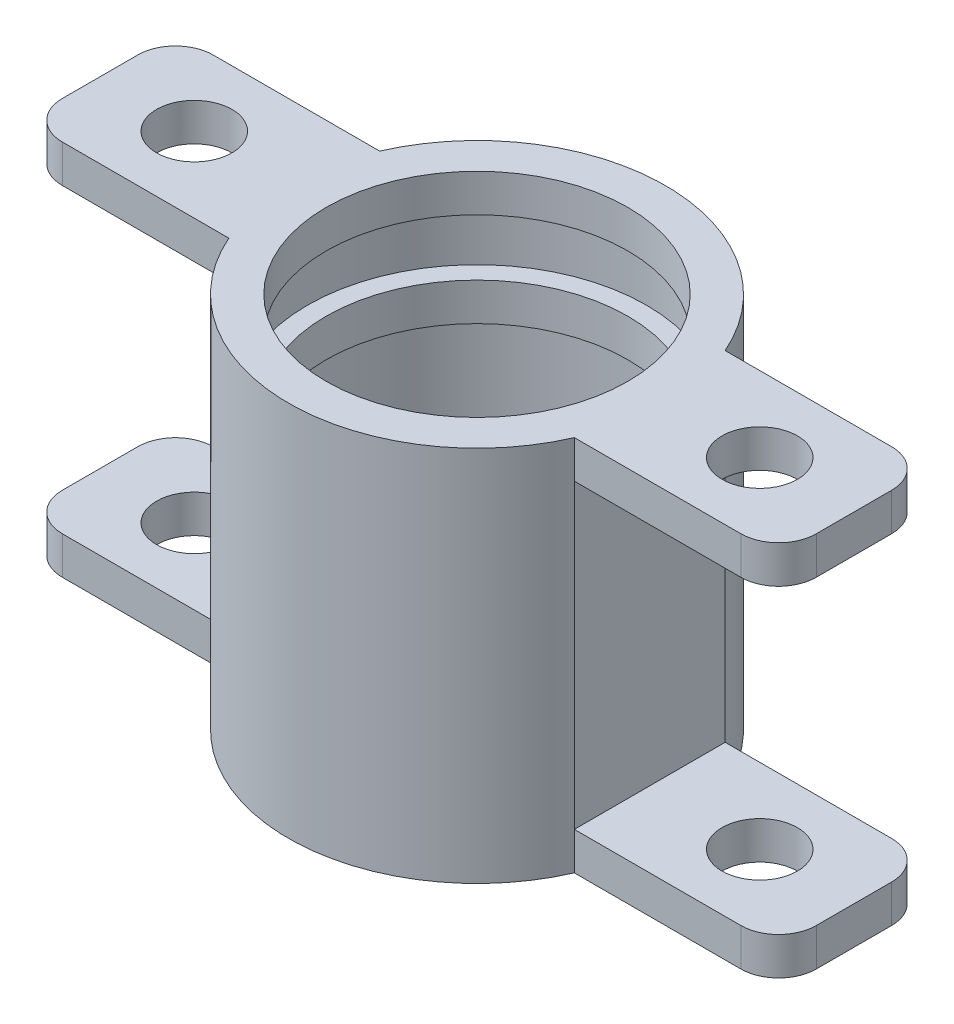
SolidWorks part; units mm, degrees
ref_plane "Front Plane" through (0, 0, 0) normal (0, 0, 1) x (1, 0, 0)
ref_plane "Top Plane" through (0, 0, 0) normal (0, 1, 0) x (1, 0, 0)
ref_plane "Right Plane" through (0, 0, 0) normal (1, 0, 0) x (0, 0, -1)
sketch "Sketch1" plane through (0, 0, 0) normal (0, 1, 0) x (1, 0, 0)
  line L0 (45.8258, 20) -> (100, 20)
  line L1 (-100, -20) -> (-45.8258, -20)
  line L2 (-100, -20) -> (-100, 20)
  line L3 (-100, 20) -> (-45.8258, 20)
  line L4 (100, -20) -> (100, 20)
  line L5 (-100, -20) -> (100, 20) construction
  line L6 (-100, 20) -> (100, -20) construction
  line L7 (45.8258, -20) -> (100, -20)
  arc A0 (-45.8258, -20) -> (45.8258, -20) centre (0, 0) ccw
  circle A1 centre (0, 0) radius 40
  arc A2 (45.8258, 20) -> (-45.8258, 20) centre (0, 0) ccw
  dimension "D1" = 100
  dimension "D2" = 80
  dimension "D3" = 200
  dimension "D4" = 40
extrude "Boss-Extrude1" add sketch "Sketch1" along normal blind 100
sketch "Sketch3" plane through (0, 0, 20) normal (0, 0, 1) x (1, 0, 0)
  line L0 (45.8258, 100) -> (100, 100) construction
  line L1 (100, 10) -> (45.8258, 10)
  line L2 (100, 10) -> (100, 90)
  line L3 (100, 90) -> (45.8258, 90)
  line L4 (45.8258, 10) -> (45.8258, 90)
  line L5 (100, 10) -> (45.8258, 90) construction
  line L6 (100, 90) -> (45.8258, 10) construction
  line L7 (45.8258, 0) -> (100, 0) construction
  line L8 (45.8258, 100) -> (45.8258, 0) construction
  line L9 (100, 100) -> (100, 0) construction
  point P0 (72.9129, 50)
  dimension "D1" = 10
  dimension "D2" = 10
extrude "Cut-Extrude1" cut sketch "Sketch3" against normal through all both and the other way through all
mirror "Mirror1" about plane through (0, 0, 0) normal (1, 0, 0) of "Cut-Extrude1"
hole_wizard "Hole1" positions "Sketch4" profile "Sketch5" legacy end condition through all
sketch "Sketch4" plane through (0, 100, 0) normal (0, 1, 0) x (1, 0, 0)
  point P0 (-75, 0)
  point P2 (75, 0)
  dimension "D1" = 150
  dimension "D2" = 75
sketch "Sketch5" plane through (-75, 100, 0) normal (1, 0, 0) x (0, 0, 1)
  line L0 (0, 0) -> (0, 100)
  line L1 (0, 100) -> (10, 100)
  line L2 (10, 100) -> (10, 0)
  line L3 (10, 0) -> (0, 0)
  line L4 (0, 110) -> (0, -10) construction
  dimension "Diameter" = 20
  dimension "Depth" = 100
fillet "Fillet1" radius 10 8 edges at (-100, 95, -20) (-100, 95, 20) (-100, 5, 20) (-100, 5, -20) (100, 5, -20) (100, 5, 20) (100, 95, -20) (100, 95, 20)
sketch "Sketch6" plane through (0, 0, 0) normal (0, 0, 1) x (1, 0, 0)
  line L0 (45.8258, 100) -> (-45.8258, 100) construction
  line L1 (0, 90) -> (45, 90)
  line L2 (0, 90) -> (0, 75)
  line L3 (0, 75) -> (45, 75)
  line L4 (45, 90) -> (45, 75)
  line L5 (0, 65) -> (45, 65)
  line L6 (0, 65) -> (0, 35)
  line L7 (0, 35) -> (45, 35)
  line L8 (45, 65) -> (45, 35)
  line L9 (0, 25) -> (45, 25)
  line L10 (0, 25) -> (0, 10)
  line L11 (0, 10) -> (45, 10)
  line L12 (45, 25) -> (45, 10)
  line L13 (-45.8258, 0) -> (45.8258, 0) construction
  line L14 (0, 0) -> (0, 100) construction
  dimension "D1" = 15
  dimension "D2" = 10
  dimension "D3" = 10
  dimension "D4" = 30
  dimension "D5" = 10
  dimension "D6" = 15
  dimension "D7" = 45
revolve "Cut-Revolve1" cut sketch "Sketch6" angle 360 about L14
